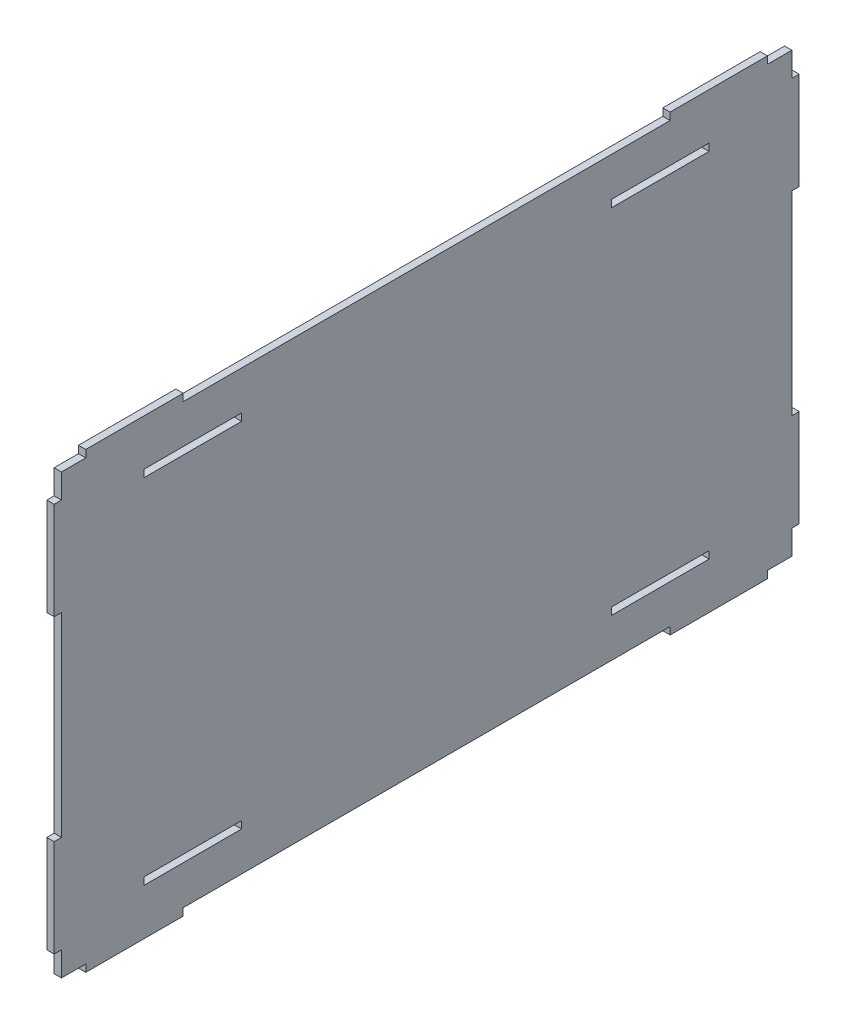
SolidWorks part; units mm, degrees
ref_plane "Front Plane" through (0, 0, 0) normal (0, 0, 1) x (1, 0, 0)
ref_plane "Top Plane" through (0, 0, 0) normal (0, 1, 0) x (1, 0, 0)
ref_plane "Right Plane" through (0, 0, 0) normal (1, 0, 0) x (0, 0, -1)
sketch "Sketch1" plane through (0, 0, 0) normal (1, 0, 0) x (0, 0, -1)
  line L1 (0, 0) -> (-300, 0)
  line L2 (0, 0) -> (0, 180)
  line L3 (0, 180) -> (-300, 180)
  line L4 (-300, 0) -> (-300, 180)
  dimension "D1" = 300
  dimension "D2" = 180
extrude "Boss-Extrude1" add sketch "Sketch1" along normal blind 3
sketch "Sketch2" plane through (3, 0, 0) normal (1, 0, 0) x (0, 0, -1)
  line L0 (0, 180) -> (-300, 180) construction
  line L1 (-290, 180) -> (-250, 180)
  line L2 (-290, 180) -> (-290, 183)
  line L3 (-290, 183) -> (-250, 183)
  line L4 (-250, 180) -> (-250, 183)
  line L5 (0, 0) -> (0, 180) construction
  line L6 (-50, 180) -> (-10, 180)
  line L7 (-50, 180) -> (-50, 183)
  line L8 (-50, 183) -> (-10, 183)
  line L9 (-10, 180) -> (-10, 183)
  line L10 (0, 170) -> (3, 170)
  line L11 (0, 170) -> (0, 130)
  line L12 (0, 130) -> (3, 130)
  line L13 (3, 170) -> (3, 130)
  line L14 (-300, 0) -> (0, 0) construction
  line L15 (0, 50) -> (3, 50)
  line L16 (0, 50) -> (0, 10)
  line L17 (0, 10) -> (3, 10)
  line L18 (3, 50) -> (3, 10)
  line L19 (-10, 0) -> (-50, 0)
  line L20 (-10, 0) -> (-10, -3)
  line L21 (-10, -3) -> (-50, -3)
  line L22 (-50, 0) -> (-50, -3)
  line L23 (-300, 180) -> (-300, 0) construction
  line L24 (-290, 0) -> (-250, 0)
  line L25 (-290, 0) -> (-290, -3)
  line L26 (-290, -3) -> (-250, -3)
  line L27 (-250, 0) -> (-250, -3)
  line L28 (-300, 170) -> (-303, 170)
  line L29 (-300, 170) -> (-300, 130)
  line L30 (-300, 130) -> (-303, 130)
  line L31 (-303, 170) -> (-303, 130)
  line L33 (-300, 50) -> (-303, 50)
  line L34 (-300, 50) -> (-300, 10)
  line L35 (-300, 10) -> (-303, 10)
  line L36 (-303, 50) -> (-303, 10)
  dimension "D1" = 3
  dimension "D2" = 40
  dimension "D3" = 40
  dimension "D4" = 40
  dimension "D5" = 3
  dimension "D6" = 10
  dimension "D7" = 10
  dimension "D8" = 10
  dimension "D9" = 10
extrude "Boss-Extrude2" add sketch "Sketch2" against normal blind 3
sketch "Sketch3" plane through (3, 0, 0) normal (1, 0, 0) x (0, 0, -1)
  line L0 (-250, 183) -> (-290, 183) construction
  line L1 (-290, -3) -> (-250, -3) construction
  line L2 (-266, 19) -> (-226, 19)
  line L3 (-266, 164) -> (-226, 164)
  line L4 (-266, 19) -> (-266, 16)
  line L5 (-266, 164) -> (-226, 164)
  line L6 (-266, 164) -> (-266, 161)
  line L7 (-266, 161) -> (-226, 161)
  line L8 (-226, 164) -> (-226, 161)
  line L9 (-266, 16) -> (-226, 16)
  line L10 (-226, 19) -> (-226, 16)
  line L11 (-10, 183) -> (-50, 183) construction
  line L12 (-77, 164) -> (-37, 164)
  line L13 (-77, 164) -> (-77, 161)
  line L14 (-77, 161) -> (-37, 161)
  line L15 (-37, 164) -> (-37, 161)
  line L16 (0, 0) -> (0, 10) construction
  line L17 (-77, 19) -> (-37, 19)
  line L18 (-77, 19) -> (-77, 16)
  line L19 (-77, 16) -> (-37, 16)
  line L20 (-37, 19) -> (-37, 16)
  line L21 (-50, -3) -> (-10, -3) construction
  dimension "D1" = 19
  dimension "D2" = 19
  dimension "D3" = 3
  dimension "D4" = 40
  dimension "D5" = 3
  dimension "D6" = 40
  dimension "D7" = 19
  dimension "D8" = 37
  dimension "D9" = 37
  dimension "D10" = 40
  dimension "D11" = 3
  dimension "D12" = 37
  dimension "D13" = 19
extrude "Cut-Extrude1" cut sketch "Sketch3" against normal through all contours L6 L7 L8 L5
sketch "Sketch4" plane through (3, 0, 0) normal (1, 0, 0) x (0, 0, -1)
  line L1 (-74, 164) -> (-34, 164)
  line L2 (-74, 164) -> (-74, 161)
  line L3 (-74, 161) -> (-34, 161)
  line L4 (-34, 164) -> (-34, 161)
  dimension "D1" = 37
  dimension "D2" = 19
  dimension "D3" = 40
  dimension "D4" = 3
extrude "Cut-Extrude2" cut sketch "Sketch4" against normal blind 3
sketch "Sketch5" plane through (3, 0, 0) normal (1, 0, 0) x (0, 0, -1)
  line L3 (-266, 19) -> (-226, 19)
  line L4 (-266, 19) -> (-266, 16)
  line L5 (-266, 16) -> (-226, 16)
  line L6 (-226, 19) -> (-226, 16)
  dimension "D1" = 37
  dimension "D2" = 19
  dimension "D3" = 3
  dimension "D4" = 40
extrude "Cut-Extrude3" cut sketch "Sketch5" against normal blind 3
sketch "Sketch6" plane through (3, 0, 0) normal (1, 0, 0) x (0, 0, -1)
  line L1 (-74, 19) -> (-34, 19)
  line L2 (-74, 19) -> (-74, 16)
  line L3 (-74, 16) -> (-34, 16)
  line L4 (-34, 19) -> (-34, 16)
  dimension "D1" = 19
  dimension "D2" = 37
  dimension "D3" = 40
  dimension "D4" = 3
extrude "Cut-Extrude4" cut sketch "Sketch6" against normal blind 3
